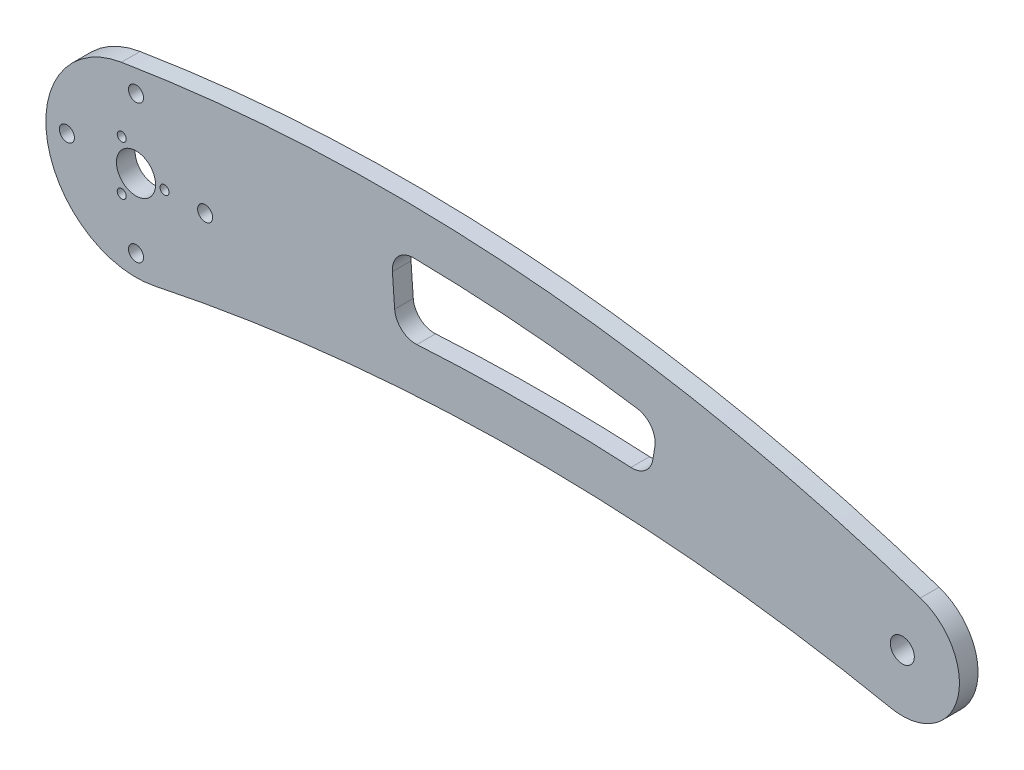
SolidWorks part; units mm, degrees
ref_plane "Front Plane" through (0, 0, 0) normal (0, 0, 1) x (1, 0, 0)
ref_plane "Top Plane" through (0, 0, 0) normal (0, 1, 0) x (1, 0, 0)
ref_plane "Right Plane" through (0, 0, 0) normal (1, 0, 0) x (0, 0, -1)
sketch "Sketch1" plane through (0, 0, 0) normal (0, 0, 1) x (1, 0, 0)
  line L4 (85.3, 14.3342) -> (86.0475, 3.8942)
  line L6 (172.6297, 7.5475) -> (171.944, 3.4452)
  circle A0 centre (254.95, -9.85) radius 4
  circle A1 centre (0, 23) radius 2.5
  circle A2 centre (0, -23) radius 2.5
  circle A3 centre (-23, 0) radius 2.5
  circle A4 centre (23, 0) radius 2.5
  circle A5 centre (0, 0) radius 6.5
  arc A8 (-4.8434, 29.6064) -> (6.1804, -29.3565) centre (0, 0) ccw
  arc A9 (260.9829, 8.1668) -> (-4.8434, 29.6064) centre (84.7592, -518.1128) ccw
  arc A11 (251.1704, -28.4703) -> (260.9829, 8.1668) centre (254.95, -9.85) ccw
  circle A45 centre (0, 0) radius 23 construction
  arc A46 (6.1804, -29.3565) -> (251.1704, -28.4703) centre (130.8185, -621.3787) cw
  arc A47 (0, 0) -> (254.95, -9.85) centre (105.6317, -570.2999) cw construction
  arc A50 (166.7889, 15.6204) -> (92.3809, 21.8334) centre (84.7592, -518.1128) ccw
  arc A58 (254.1543, -13.7701) -> (256.2201, -6.057) centre (254.95, -9.85) ccw construction
  arc A59 (-2.4217, 14.8032) -> (3.0902, -14.6782) centre (0, 0) ccw construction
  arc A60 (256.2201, -6.057) -> (-2.4217, 14.8032) centre (84.7592, -518.1128) ccw construction
  arc A61 (93.4516, -2.5932) -> (164.6577, -2.3902) centre (130.8185, -621.3787) cw
  arc A62 (3.0902, -14.6782) -> (254.1543, -13.7701) centre (130.8185, -621.3787) cw construction
  arc A63 (172.6297, 7.5475) -> (166.7889, 15.6204) centre (165.7255, 8.7016) ccw
  arc A64 (171.944, 3.4452) -> (164.6577, -2.3902) centre (165.0398, 4.5993) cw
  arc A65 (86.0475, 3.8942) -> (93.4516, -2.5932) centre (93.0296, 4.3941) ccw
  arc A66 (85.3, 14.3342) -> (92.3809, 21.8334) centre (92.2821, 14.8341) cw
  point P33 (173.7914, 14.497)
  point P36 (170.9061, -2.7635)
  point P39 (86.5447, -3.049)
  point P42 (84.7592, 21.8872)
  dimension "D1" = 13
  dimension "D2" = 46
  dimension "D3" = 5
  dimension "D4" = 30
  dimension "D7" = 8
  dimension "D8" = 19
  dimension "D9" = 605
  dimension "D10" = 555
  dimension "D11" = 580
  dimension "D14" = 17.5
  dimension "D15" = 7
  dimension "D5" = 254.95
  dimension "D6" = 9.85
  dimension "D13" = 25
  dimension "D12" = 15
extrude "Boss-Extrude1" add sketch "Sketch1" along normal blind 6.2
sketch "Sketch2" plane through (0, 0, 6.2) normal (0, 0, 1) x (1, 0, 0)
  circle A0 centre (-4.75, -8.2272) radius 1.5 construction
  circle A1 centre (-4.75, 8.2272) radius 1.5 construction
  circle A2 centre (9.5, 0) radius 1.5 construction
  circle A3 centre (-4.75, -8.2272) radius 1.5
  circle A4 centre (-4.75, 8.2272) radius 1.5
  circle A5 centre (9.5, 0) radius 1.5
extrude "Cut-Extrude1" cut sketch "Sketch2" against normal up to next
